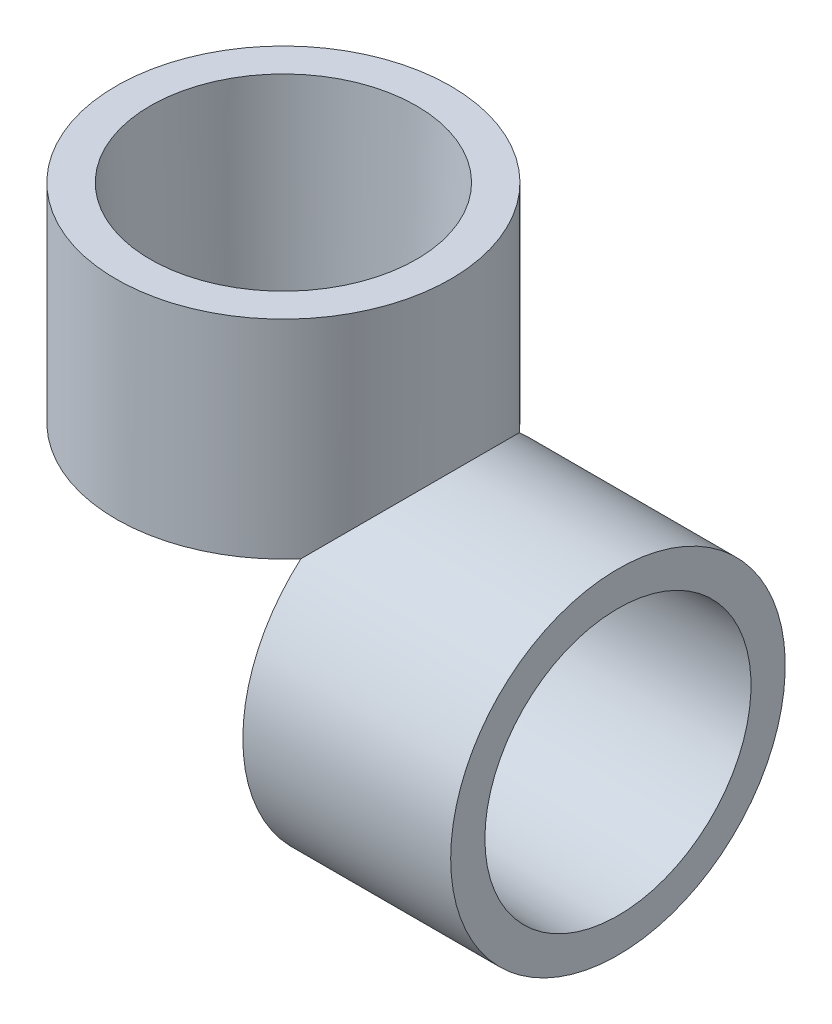
SolidWorks part; units mm, degrees
ref_plane "Front Plane" through (0, 0, 0) normal (0, 0, 1) x (1, 0, 0)
ref_plane "Top Plane" through (0, 0, 0) normal (0, 1, 0) x (1, 0, 0)
ref_plane "Right Plane" through (0, 0, 0) normal (1, 0, 0) x (0, 0, -1)
sketch "Sketch1" plane through (0, 0, 0) normal (0, 0, 1) x (1, 0, 0)
  line L0 (-22.4024, 0) -> (22.4024, 0) construction
  line L1 (12.7, -12.6873) -> (33.528, -13.335)
  line L4 (12.7, -12.6873) -> (12.7, -16.764)
  line L5 (12.7, -16.764) -> (33.528, -16.764)
  line L6 (33.528, -16.764) -> (33.528, -13.335)
  point P4 (0, 0)
  dimension "D1" = 3.429
  dimension "D2" = 4.0767
  dimension "D3" = 20.828
  dimension "D4" = 16.764
  dimension "D5" = 12.7
revolve "Revolve1" add sketch "Sketch1" angle 360 about L0
sketch "Sketch2" plane through (0, 0, 0) normal (0, 0, 1) x (1, 0, 0)
  line L0 (-16.764, 33.528) -> (-16.764, 12.7)
  line L1 (-16.764, 12.7) -> (-12.6873, 12.7)
  line L2 (-12.6873, 12.7) -> (-13.335, 33.528)
  line L3 (-13.335, 33.528) -> (-16.764, 33.528)
  line L4 (0, 0) -> (0, 51.903) construction
  dimension "D1" = 12.7
  dimension "D2" = 20.828
  dimension "D3" = 16.764
  dimension "D4" = 3.429
  dimension "D5" = 4.0767
revolve "Revolve2" add sketch "Sketch2" angle 360 about L4
sketch "Sketch5" plane through (12.7, 0, 0) normal (-1, 0, 0) x (0, 0, 1)
  circle A0 centre (0, 0) radius 12.6873
  circle A1 centre (0, 0) radius 16.764
  dimension "D1" = 33.528
  dimension "D2" = 25.3746
sketch "Sketch3" plane through (0, 0, 0) normal (0, 0, 1) x (1, 0, 0)
  line L0 (0, 33.528) -> (0, -34.5209) construction
  line L1 (16.764, 33.528) -> (-16.764, 33.528) construction
  line L3 (33.528, 0) -> (-28.1635, 0) construction
  line L4 (33.528, -16.764) -> (33.528, 16.764) construction
  arc A0 (0, 12.7) -> (12.7, 0) centre (12.7, 12.7) ccw
